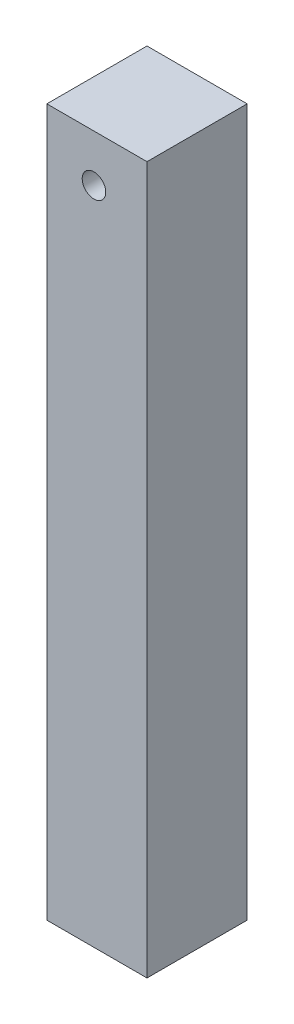
SolidWorks part; units mm, degrees
material "1060 Alloy"
ref_plane "Front Plane" through (0, 0, 0) normal (0, 0, 1) x (1, 0, 0)
ref_plane "Top Plane" through (0, 0, 0) normal (0, 1, 0) x (1, 0, 0)
ref_plane "Right Plane" through (0, 0, 0) normal (1, 0, 0) x (0, 0, -1)
sketch "Sketch1" plane through (0, 0, 0) normal (0, 1, 0) x (1, 0, 0)
  line L1 (0, 0) -> (21.59, 0)
  line L2 (0, 0) -> (0, -21.59)
  line L3 (0, -21.59) -> (21.59, -21.59)
  line L4 (21.59, 0) -> (21.59, -21.59)
  line L5 (0, 0) -> (21.59, -21.59) construction
  line L6 (0, -21.59) -> (21.59, 0) construction
  point P4 (10.795, -10.795)
  dimension "D1" = 21.59
  dimension "D2" = 21.59
extrude "Boss-Extrude1" add sketch "Sketch1" along normal blind 152.4
sketch "Sketch2" plane through (0, 0, 0) normal (0, 0, 1) x (1, 0, 0)
  circle A0 centre (10.16, 142.24) radius 2.54
extrude "Cut-Extrude1" cut sketch "Sketch2" along normal blind 26.67
